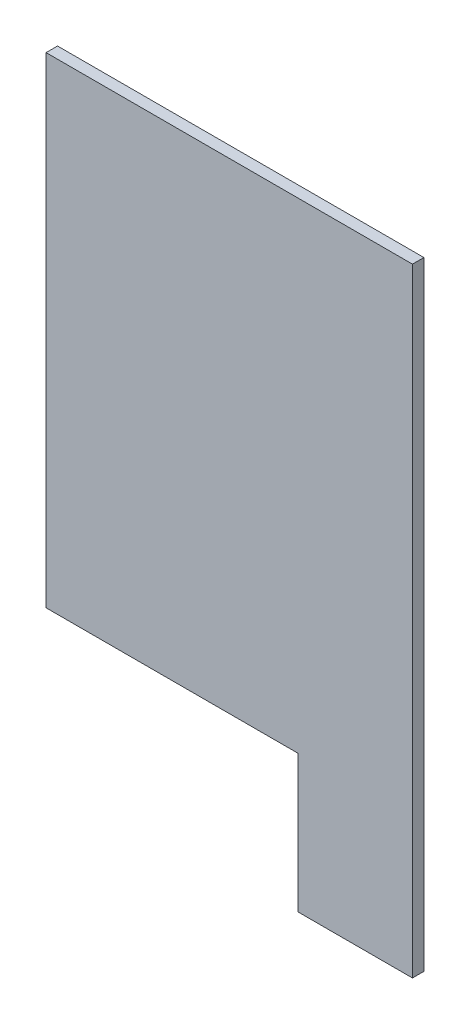
SolidWorks part; units mm, degrees
ref_plane "Front Plane" through (0, 0, 0) normal (0, 0, 1) x (1, 0, 0)
ref_plane "Top Plane" through (0, 0, 0) normal (0, 1, 0) x (1, 0, 0)
ref_plane "Right Plane" through (0, 0, 0) normal (1, 0, 0) x (0, 0, -1)
sketch "Sketch1" plane through (0, 0, 0) normal (0, 0, 1) x (1, 0, 0)
  line L0 (0, -210) -> (110, -210)
  line L1 (0, 0) -> (160, 0)
  line L2 (0, 0) -> (0, -210)
  line L3 (110, -270) -> (160, -270)
  line L4 (160, 0) -> (160, -270)
  line L5 (110, -210) -> (110, -270)
  dimension "D1" = 160
  dimension "D2" = 270
  dimension "D3" = 210
  dimension "D4" = 110
extrude "Boss-Extrude1" add sketch "Sketch1" along normal blind 5
